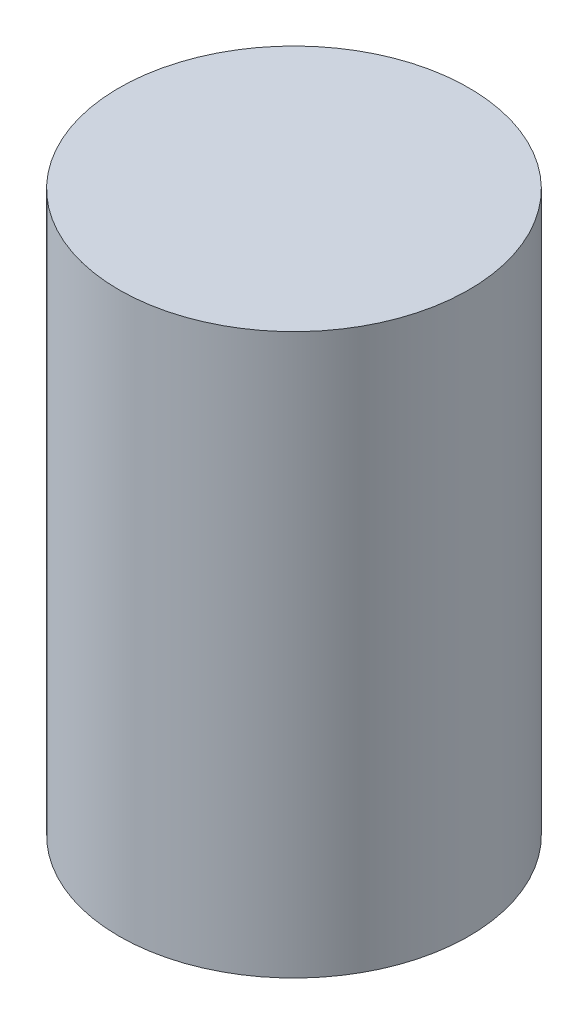
SolidWorks part; units mm, degrees
ref_plane "前视基准面" through (0, 0, 0) normal (0, 0, 1) x (1, 0, 0)
ref_plane "上视基准面" through (0, 0, 0) normal (0, 1, 0) x (1, 0, 0)
ref_plane "右视基准面" through (0, 0, 0) normal (1, 0, 0) x (0, 0, -1)
sketch "草图1" plane through (0, 0, 0) normal (0, 1, 0) x (1, 0, 0)
  circle A0 centre (0, 0) radius 2.5
  dimension "D1" = 5
extrude "凸台-拉伸1" add sketch "草图1" along normal blind 8
